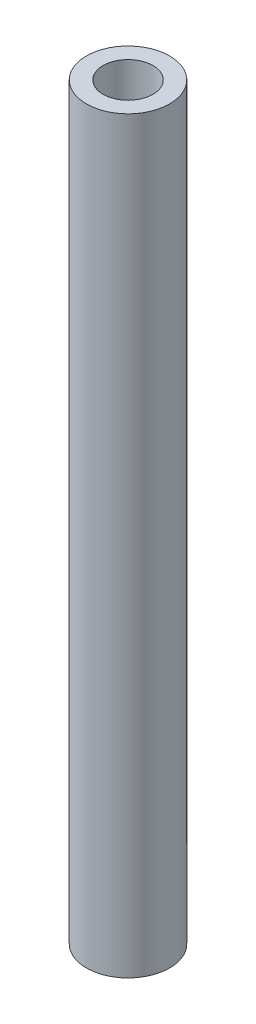
SolidWorks part; units mm, degrees
ref_plane "前视基准面" through (0, 0, 0) normal (0, 0, 1) x (1, 0, 0)
ref_plane "上视基准面" through (0, 0, 0) normal (0, 1, 0) x (1, 0, 0)
ref_plane "右视基准面" through (0, 0, 0) normal (1, 0, 0) x (0, 0, -1)
other "Configuration Table"
sketch "草图1" plane through (0, 0, 0) normal (0, 1, 0) x (1, 0, 0)
  circle A0 centre (0, 0) radius 1.5
  circle A1 centre (0, 0) radius 2.5
  dimension "D1" = 3
  dimension "D2" = 5
extrude "凸台-拉伸1" add sketch "草图1" along normal blind 45
